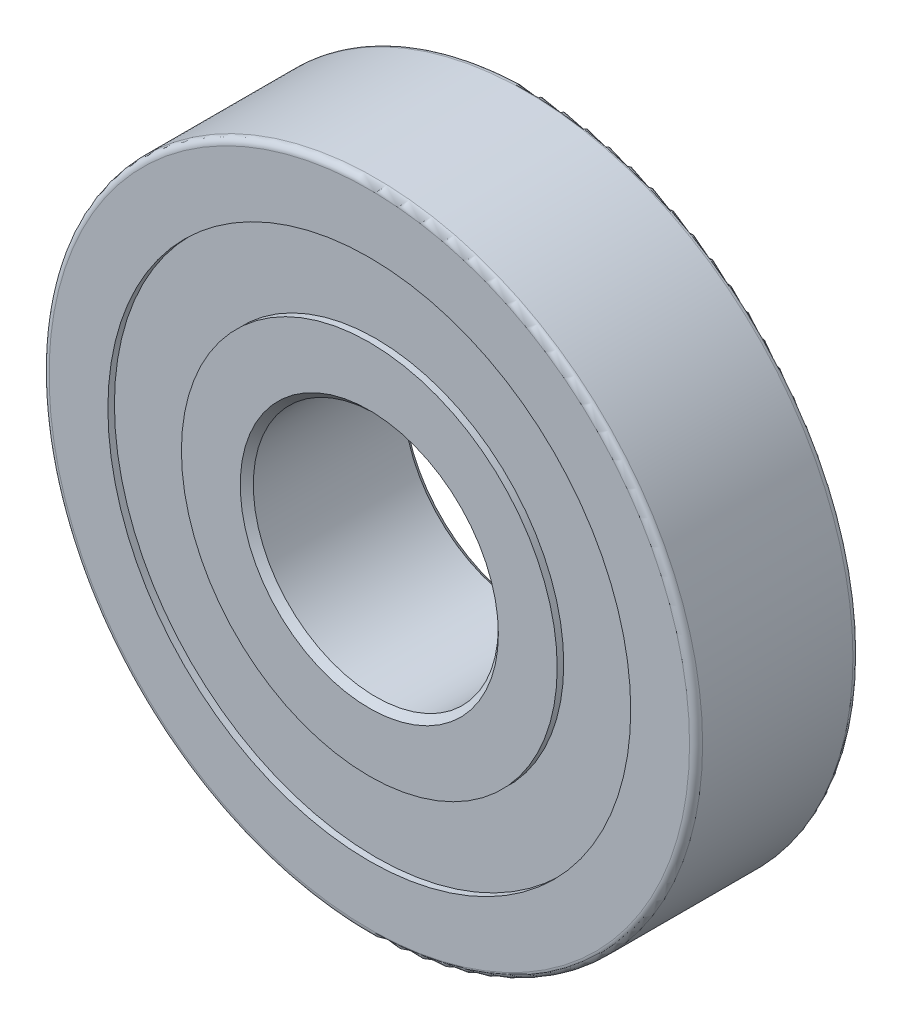
SolidWorks part; units mm, degrees
ref_plane "Front Plane" through (0, 0, 0) normal (0, 0, 1) x (1, 0, 0)
ref_plane "Top Plane" through (0, 0, 0) normal (0, 1, 0) x (1, 0, 0)
ref_plane "Right Plane" through (0, 0, 0) normal (1, 0, 0) x (0, 0, -1)
sketch "Sketch1" plane through (0, 0, 0) normal (0, 0, 1) x (1, 0, 0)
  circle A0 centre (0, 0) radius 2.3813
  circle A1 centre (0, 0) radius 6.35
  circle A2 centre (0, 0) radius 5.08
  circle A3 centre (0, 0) radius 3.6513
  dimension "D1" = 12.7
  dimension "D2" = 4.7625
  dimension "D3" = 1.27
  dimension "D4" = 1.27
extrude "Boss-Extrude1" add sketch "Sketch1" along normal mid plane 3.175 contours A1 A2 | A3 A0
sketch "Sketch2" plane through (0, 0, 0) normal (0, 0, 1) x (1, 0, 0)
  circle A0 centre (0, 0) radius 6.35
  circle A1 centre (0, 0) radius 5.08
  circle A2 centre (0, 0) radius 5.08
  circle A3 centre (0, 0) radius 6.35 construction
  circle A4 centre (0, 0) radius 3.6513
  circle A5 centre (0, 0) radius 3.6513
extrude "Boss-Extrude2" add sketch "Sketch2" along normal mid plane 2.921
fillet "Fillet1" radius 0.127 2 edges at (6.35, 0, -1.5875) (6.35, 0, 1.5875)
chamfer "Chamfer1" distance 0.127 2 edges at (2.3813, 0, -1.5875) (2.3813, 0, 1.5875)
